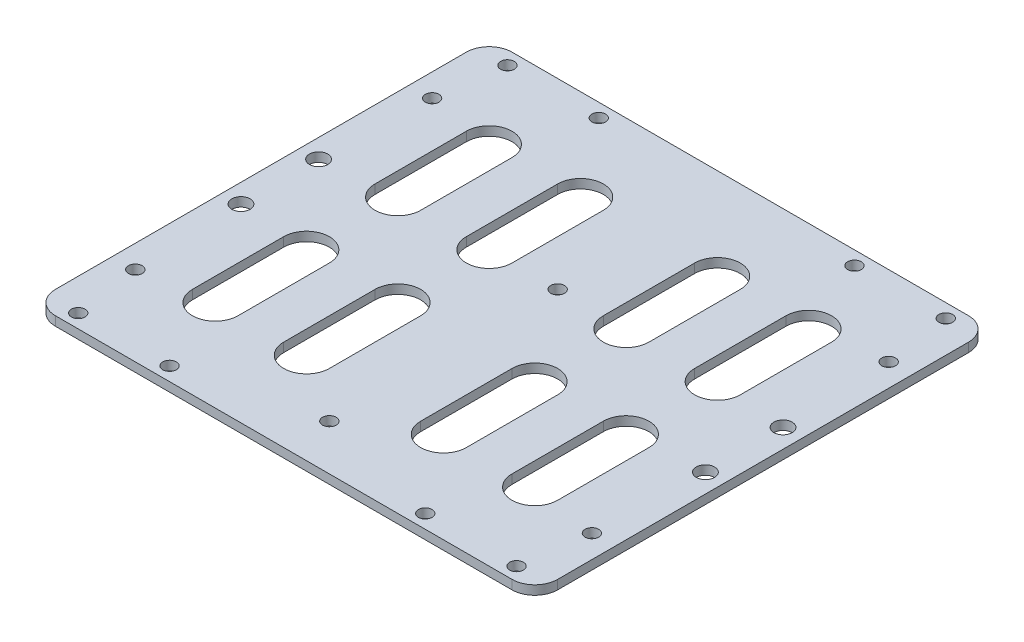
SolidWorks part; units mm, degrees
ref_plane "前视基准面" through (0, 0, 0) normal (0, 0, 1) x (1, 0, 0)
ref_plane "上视基准面" through (0, 0, 0) normal (0, 1, 0) x (1, 0, 0)
ref_plane "右视基准面" through (0, 0, 0) normal (1, 0, 0) x (0, 0, -1)
other "Configuration Table"
sketch "草图1" plane through (0, 0, 0) normal (0, 1, 0) x (1, 0, 0)
  line L0 (-48, -47) -> (-28, -47) construction
  line L1 (-55, 50) -> (55, 50)
  line L2 (-55, 50) -> (-55, -50)
  line L3 (-55, -50) -> (55, -50)
  line L4 (55, 50) -> (55, -50)
  line L5 (-55, 50) -> (55, -50) construction
  line L6 (-55, -50) -> (55, 50) construction
  line L7 (0, 0) -> (0, -50) construction
  line L8 (-50.8546, 8.5) -> (-50.8546, -8.5) construction
  line L9 (-50.8546, 0) -> (0, 0) construction
  circle A0 centre (-48, -47) radius 1.5
  circle A1 centre (-28, -47) radius 1.5
  circle A2 centre (28, -47) radius 1.5
  circle A3 centre (48, -47) radius 1.5
  circle A4 centre (-50.8546, 8.5) radius 2
  circle A5 centre (-50.8546, -8.5) radius 2
  circle A6 centre (50.8546, -8.5) radius 2
  circle A7 centre (50.8546, 8.5) radius 2
  circle A8 centre (48, 47) radius 1.5
  circle A9 centre (28, 47) radius 1.5
  circle A10 centre (-28, 47) radius 1.5
  circle A11 centre (-48, 47) radius 1.5
  point P0 (0, 0)
  dimension "D2" = 3
  dimension "D8" = 4
  dimension "D1" = 20
  dimension "D3" = 3
  dimension "D4" = 28
  dimension "D5" = 110
  dimension "D6" = 100
  dimension "D7" = 17
  dimension "D9" = 4.1454
extrude "凸台-拉伸1" add sketch "草图1" along normal blind 2
fillet "圆角1" radius 5 4 edges at (55, 1, 50) (-55, 1, 50) (55, 1, -50) (-55, 1, -50)
sketch "草图2" plane through (0, 2, 0) normal (0, 1, 0) x (1, 0, 0)
  line L0 (0, 0) -> (0, -50) construction
  line L1 (-50, -50) -> (50, -50) construction
  line L2 (0, 0) -> (0, 50) construction
  line L3 (50, 50) -> (-50, 50) construction
  circle A0 centre (0, 10) radius 1.5
  circle A1 centre (0, -40) radius 1.5
  dimension "D3" = 3
  dimension "D1" = 50
  dimension "D2" = 10
extrude "铝管安装孔" cut sketch "草图2" against normal blind 10
sketch "草图3" plane through (0, 0, 0) normal (0, -1, 0) x (1, 0, 0)
  line L0 (35, -30) -> (35, -10) construction
  line L1 (30, -30) -> (30, -10)
  line L2 (40, -30) -> (40, -10)
  line L3 (15, -30) -> (15, -10) construction
  line L4 (10, -30) -> (10, -10)
  line L5 (20, -30) -> (20, -10)
  line L6 (0, 0) -> (0, 50) construction
  line L7 (-50, 50) -> (50, 50) construction
  line L8 (0, 0) -> (55, 0) construction
  line L9 (55, 45) -> (55, -45) construction
  line L10 (35, 30) -> (35, 10) construction
  line L11 (30, 30) -> (30, 10)
  line L12 (40, 30) -> (40, 10)
  line L13 (15, 30) -> (15, 10) construction
  line L14 (10, 30) -> (10, 10)
  line L15 (20, 30) -> (20, 10)
  line L16 (-35, -30) -> (-35, -10) construction
  line L17 (-30, -30) -> (-30, -10)
  line L18 (-40, -30) -> (-40, -10)
  line L19 (-15, -30) -> (-15, -10) construction
  line L20 (-10, -30) -> (-10, -10)
  line L21 (-20, -30) -> (-20, -10)
  line L22 (-35, 30) -> (-35, 10) construction
  line L23 (-30, 30) -> (-30, 10)
  line L24 (-40, 30) -> (-40, 10)
  line L25 (-15, 30) -> (-15, 10) construction
  line L26 (-10, 30) -> (-10, 10)
  line L27 (-20, 30) -> (-20, 10)
  arc A0 (30, -30) -> (40, -30) centre (35, -30) ccw
  arc A1 (40, -10) -> (30, -10) centre (35, -10) ccw
  arc A2 (10, -30) -> (20, -30) centre (15, -30) ccw
  arc A3 (20, -10) -> (10, -10) centre (15, -10) ccw
  arc A4 (30, 30) -> (40, 30) centre (35, 30) cw
  arc A5 (40, 10) -> (30, 10) centre (35, 10) cw
  arc A6 (10, 30) -> (20, 30) centre (15, 30) cw
  arc A7 (20, 10) -> (10, 10) centre (15, 10) cw
  arc A8 (-30, -30) -> (-40, -30) centre (-35, -30) cw
  arc A9 (-40, -10) -> (-30, -10) centre (-35, -10) cw
  arc A10 (-10, -30) -> (-20, -30) centre (-15, -30) cw
  arc A11 (-20, -10) -> (-10, -10) centre (-15, -10) cw
  arc A12 (-30, 30) -> (-40, 30) centre (-35, 30) ccw
  arc A13 (-40, 10) -> (-30, 10) centre (-35, 10) ccw
  arc A14 (-10, 30) -> (-20, 30) centre (-15, 30) ccw
  arc A15 (-20, 10) -> (-10, 10) centre (-15, 10) ccw
  point P2 (35, -20)
  point P7 (15, -20)
  point P26 (35, 20)
  point P33 (15, 20)
  point P40 (-35, -20)
  point P47 (-15, -20)
  point P54 (-35, 20)
  point P61 (-15, 20)
  dimension "D1" = 5
  dimension "D2" = 10
  dimension "D3" = 10
  dimension "D4" = 20
  dimension "D5" = 10
extrude "减重" cut sketch "草图3" against normal blind 10
sketch "草图4" plane through (0, 0, 0) normal (0, -1, 0) x (1, 0, 0)
  line L0 (0, 0) -> (0, 50) construction
  line L1 (-50, 50) -> (50, 50) construction
  line L2 (0, 0) -> (-55, 0) construction
  line L3 (-55, -45) -> (-55, 45) construction
  line L4 (55, 45) -> (55, -45) construction
  circle A0 centre (50, 32.5) radius 1.5
  circle A1 centre (-50, 32.5) radius 1.5
  circle A2 centre (-50, -32.5) radius 1.5
  circle A3 centre (50, -32.5) radius 1.5
  point P14 (45.4734, 38.0276)
  dimension "D1" = 3
  dimension "D2" = 5
  dimension "D3" = 17.5
extrude "裙边安装孔" cut sketch "草图4" against normal blind 10
